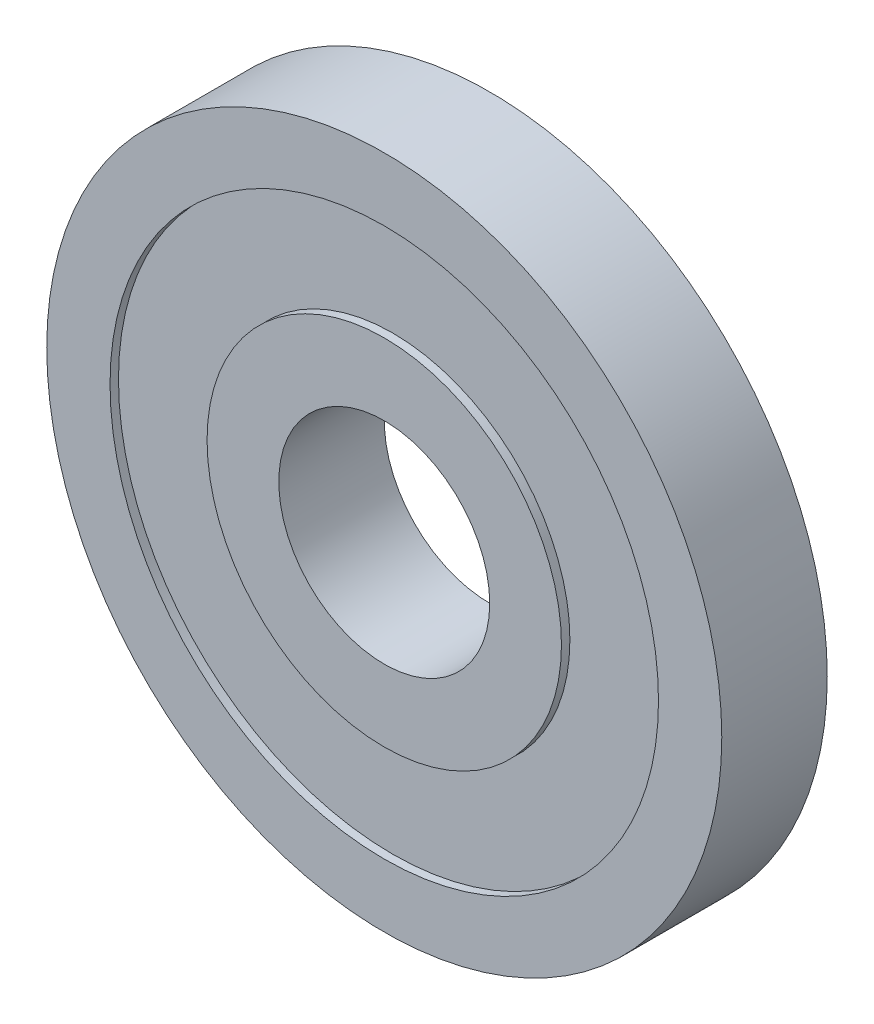
SolidWorks part; units mm, degrees
ref_plane "Alzado" through (0, 0, 0) normal (0, 0, 1) x (1, 0, 0)
ref_plane "Planta" through (0, 0, 0) normal (0, 1, 0) x (1, 0, 0)
ref_plane "Vista lateral" through (0, 0, 0) normal (1, 0, 0) x (0, 0, -1)
sketch "Croquis1" plane through (0, 0, 0) normal (0, 1, 0) x (1, 0, 0)
  line L0 (0, 0) -> (2.5, 0) construction
  line L5 (2.5, 2.3) -> (2.5, 2.5)
  line L8 (2.5, 2.5) -> (4.2, 2.5)
  line L9 (2.5, 2.3) -> (2.5, 0)
  line L10 (4.2, 2.5) -> (4.2, 2.3)
  line L11 (4.2, 2.3) -> (6.5, 2.3)
  line L12 (6.5, 2.3) -> (6.5, 2.5)
  line L13 (6.5, 2.5) -> (8, 2.5)
  line L14 (8, 2.5) -> (8, 0)
  line L15 (8, 0) -> (6.5, 0)
  line L16 (0, 0) -> (0, 2.5) construction
  line L17 (0, 2.5) -> (2.5, 2.5) construction
  line L18 (4.2, 0) -> (4.2, 0.2)
  line L19 (4.2, 0.2) -> (6.5, 0.2)
  line L20 (6.5, 0.2) -> (6.5, 0)
  line L21 (4.2, 0) -> (2.5, 0)
  dimension "D1" = 2.3
  dimension "D2" = 1.5
  dimension "D3" = 1.7
  dimension "D4" = 8
  dimension "D5" = 0.2
revolve "Revolución1" add sketch "Croquis1" angle 360 about L16
